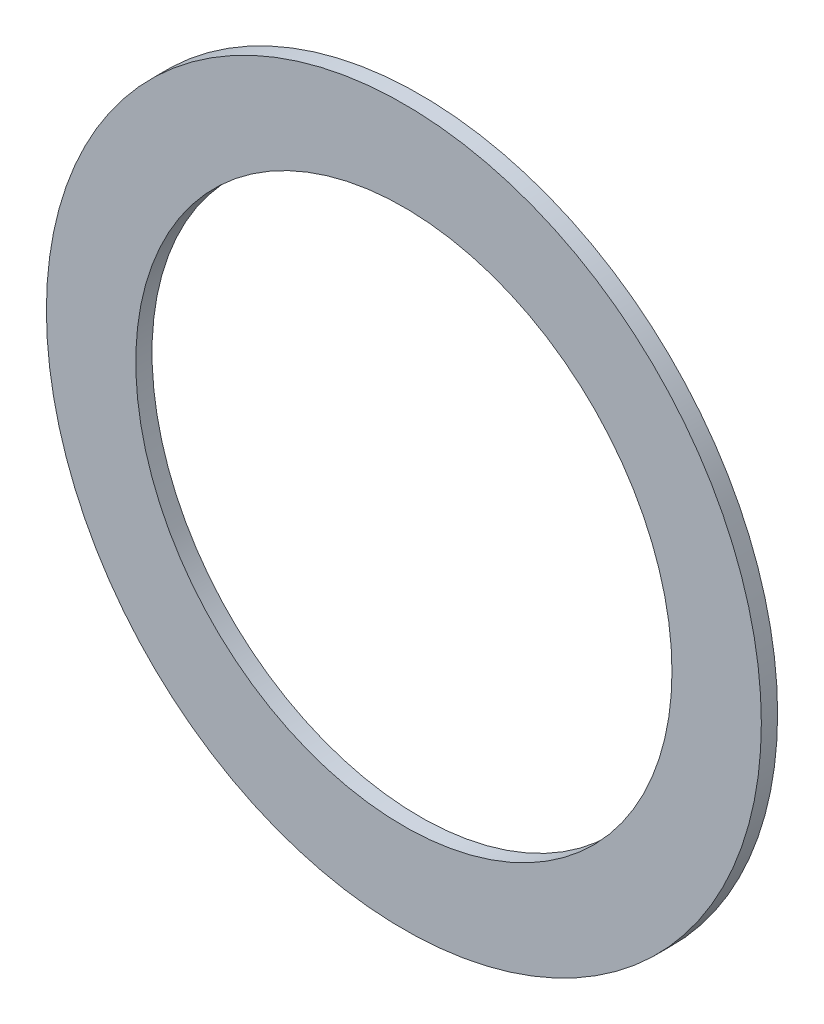
SolidWorks part; units mm, degrees
material "HYPALON"
ref_plane "Front Plane" through (0, 0, 0) normal (0, 0, 1) x (1, 0, 0)
ref_plane "Top Plane" through (0, 0, 0) normal (0, 1, 0) x (1, 0, 0)
ref_plane "Right Plane" through (0, 0, 0) normal (1, 0, 0) x (0, 0, -1)
sketch "Sketch1" plane through (0, 0, 0) normal (0, 0, 1) x (1, 0, 0)
  circle A0 centre (0, 0) radius 8.25
  circle A1 centre (0, 0) radius 11
  dimension "D1" = 16.5
  dimension "D2" = 22
extrude "Boss-Extrude1" add sketch "Sketch1" along normal blind 0.5 and the other way blind 0.0001
